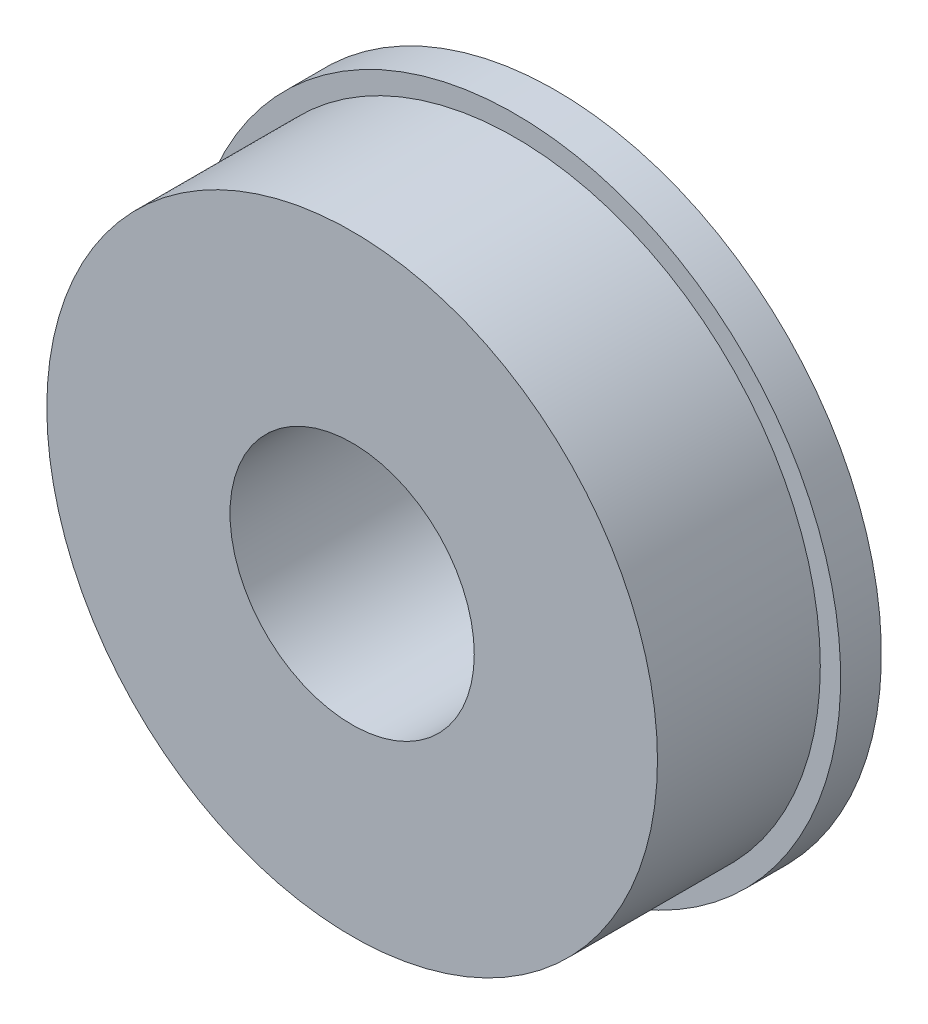
SolidWorks part; units mm, degrees
ref_plane "Front Plane" through (0, 0, 0) normal (0, 0, 1) x (1, 0, 0)
ref_plane "Top Plane" through (0, 0, 0) normal (0, 1, 0) x (1, 0, 0)
ref_plane "Right Plane" through (0, 0, 0) normal (1, 0, 0) x (0, 0, -1)
sketch "Sketch1" plane through (0, 0, 0) normal (0, 0, 1) x (1, 0, 0)
  circle A0 centre (0, 0) radius 7.5
  circle A1 centre (0, 0) radius 3
  dimension "D1" = 15
  dimension "D2" = 6
extrude "Boss-Extrude1" add sketch "Sketch1" along normal blind 5
sketch "Sketch2" plane through (0, 0, 0) normal (0, 0, -1) x (-1, 0, 0)
  circle A0 centre (0, 0) radius 7.5
  circle A1 centre (0, 0) radius 8
  dimension "D1" = 15
  dimension "D2" = 16
extrude "Boss-Extrude2" add sketch "Sketch2" against normal blind 1
